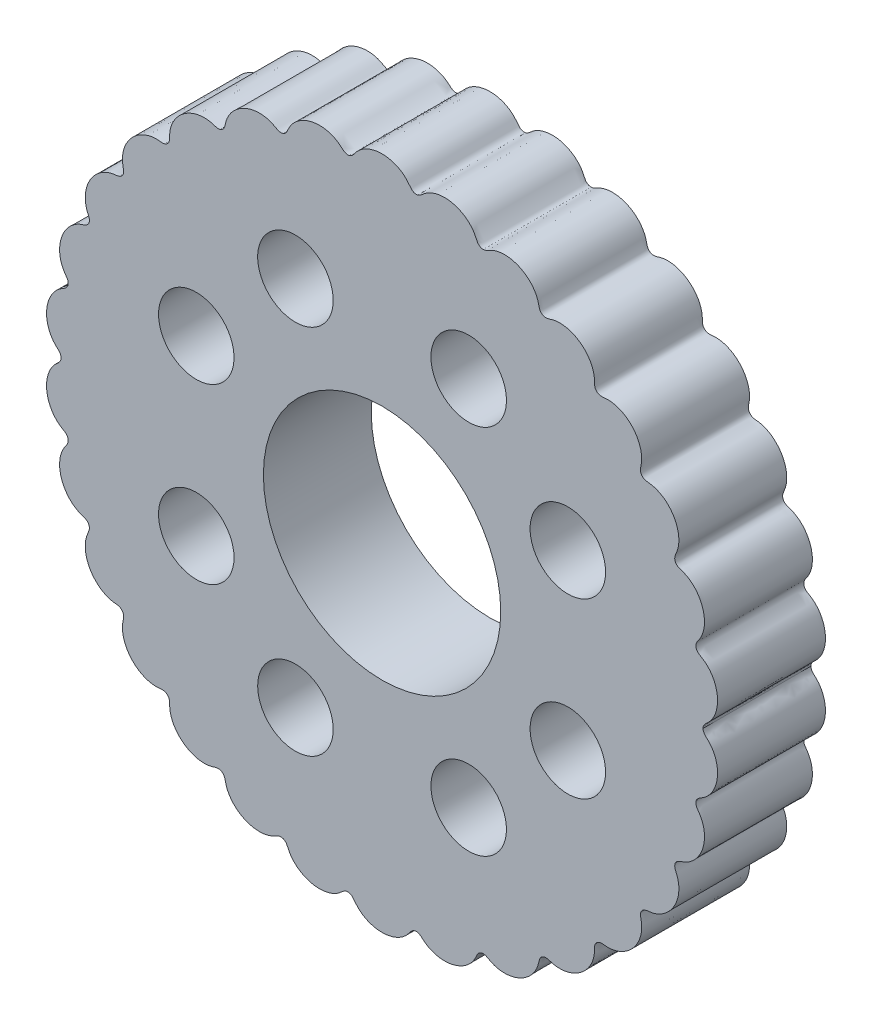
SolidWorks part; units mm, degrees
ref_plane "Plan de face" through (0, 0, 0) normal (0, 0, 1) x (1, 0, 0)
ref_plane "Plan de dessus" through (0, 0, 0) normal (0, 1, 0) x (1, 0, 0)
ref_plane "Plan de droite" through (0, 0, 0) normal (1, 0, 0) x (0, 0, -1)
sketch "Esquisse1" plane through (0, 0, 0) normal (0, 0, 1) x (1, 0, 0)
  line L0 (-1000, 0) -> (49000, 0) construction
  spline S0 degree 4 poles (29.8631, 8.2305) (29.8499, 8.1217) (29.8133, 7.9053) (29.7416, 7.64) (29.6157, 7.3353) (29.4839, 7.095) (29.3642, 6.911) (29.2467, 6.7537) (29.1538, 6.6056) (29.0902, 6.432) (29.0737, 6.2397) (29.1354, 6.023) (29.2904, 5.838) (29.4774, 5.7198) (29.6579, 5.6163) (29.8231, 5.5082) (30.0196, 5.3594) (30.2372, 5.1583) (30.5232, 4.8242) (30.8216, 4.3213) (31.0469, 3.679) (31.1337, 2.9091) (31.0567, 2.2277) (30.8902, 1.7108) (30.7109, 1.353) (30.5728, 1.1334) (30.4496, 0.9663) (30.3139, 0.8094) (30.1671, 0.6626) (30.0393, 0.549) (29.9425, 0.4546) (29.8803, 0.3777) (29.8449, 0.3262) (29.8141, 0.2716) (29.7888, 0.2141) (29.7717, 0.1632) (29.761, 0.1169) (29.7536, 0.0672) (29.7495, 0.017) (29.7494, -0.0206) (29.7556, -0.0898) (29.7678, -0.1499) (29.7904, -0.2203) (29.8284, -0.303) (29.8828, -0.3847) (29.9529, -0.4642) (30.04, -0.5488) (30.1416, -0.6407) (30.2572, -0.7512) (30.3813, -0.8854) (30.4962, -1.0277) (30.6276, -1.2147) (30.7721, -1.4641) (30.9126, -1.7829) (31.0276, -2.1744) (31.0935, -2.591) (31.107, -3.0187) (31.0662, -3.4508) (30.9693, -3.8803) (30.8145, -4.2991) (30.6117, -4.6792) (30.3965, -4.9766) (30.1917, -5.1998) (30.0146, -5.3603) (29.8643, -5.4786) (29.7061, -5.5858) (29.542, -5.684) (29.3671, -5.785) (29.2042, -5.9269) (29.0936, -6.1295) (29.0703, -6.371) (29.1391, -6.5914) (29.2598, -6.7697) (29.3791, -6.934) (29.4834, -7.0955) (29.5997, -7.3056) (29.715, -7.5703) (29.8147, -7.8969) (29.8798, -8.2857) (29.896, -8.684) (29.8631, -9.0858) (29.7829, -9.4799) (29.6574, -9.8612) (29.4885, -10.2243) (29.2783, -10.5643) (29.0303, -10.8742) (28.7824, -11.1148) (28.5506, -11.2952) (28.3468, -11.4258) (28.1768, -11.5188) (28.0006, -11.599) (27.8193, -11.6676) (27.6244, -11.7296) (27.4217, -11.8089) (27.242, -11.9571) (27.1301, -12.1734) (27.113, -12.404) (27.1707, -12.6114) (27.2542, -12.795) (27.3276, -12.9715) (27.3906, -13.1518) (27.4404, -13.3363) (27.4866, -13.5706) (27.5177, -13.8717) (27.5133, -14.2384) (27.4499, -14.6642) (27.3252, -15.0926) (27.1465, -15.4978) (26.919, -15.8739) (26.6474, -16.2153) (26.3365, -16.5168) (26.0024, -16.764) (25.654, -16.9563) (25.3418, -17.0779) (25.0791, -17.148) (24.8562, -17.1866) (24.6765, -17.2082) (24.4854, -17.2287) (24.2872, -17.2853) (24.1038, -17.4139) (23.9758, -17.6159) (23.9376, -17.8434) (23.9703, -18.0586) (24.0141, -18.2584) (24.0453, -18.4498) (24.0639, -18.6424) (24.0684, -18.8361) (24.0572, -19.0779) (24.0169, -19.3689) (23.9324, -19.7039) (23.7881, -20.0736) (23.5988, -20.4256) (23.3687, -20.7534) (23.1013, -21.0528) (22.8001, -21.3193) (22.4685, -21.5487) (22.1155, -21.7338) (21.7463, -21.8718) (21.4135, -21.9488) (21.1267, -21.9813) (20.8866, -21.9856) (20.6945, -21.9761) (20.4927, -21.9549) (20.2778, -21.9395) (20.0526, -21.9901) (19.8551, -22.131) (19.7349, -22.3281) (19.6935, -22.5401) (19.6935, -22.7421) (19.6905, -22.9333) (19.6768, -23.124) (19.6495, -23.3133) (19.599, -23.5469) (19.5081, -23.8358) (19.3582, -24.1709) (19.1304, -24.5365) (18.8451, -24.88) (18.5216, -25.1787) (18.1677, -25.4301) (17.7906, -25.6322) (17.3968, -25.7835) (17.0003, -25.8796) (16.6085, -25.9224) (16.2742, -25.9148) (16.002, -25.8785) (15.7793, -25.8278) (15.6036, -25.7769) (15.4169, -25.7147) (15.2087, -25.6689) (14.9779, -25.6954) (14.7639, -25.8189) (14.6256, -26.0056) (14.5611, -26.2088) (14.5217, -26.4015) (14.4779, -26.5791) (14.4104, -26.7974) (14.3058, -27.0513) (14.1452, -27.3445) (13.9122, -27.6625) (13.6308, -27.9579) (13.3029, -28.2232) (12.9393, -28.4488) (12.5446, -28.6295) (12.1242, -28.7604) (11.6841, -28.8357) (11.2535, -28.8501) (10.8884, -28.8124) (10.5927, -28.7466) (10.3651, -28.6736) (10.1875, -28.6026) (10.0156, -28.5191) (9.8485, -28.4261) (9.6736, -28.3252) (9.4693, -28.255) (9.2385, -28.2605) (9.0177, -28.3611) (8.8612, -28.5309) (8.7671, -28.7246) (8.6846, -28.91) (8.5968, -29.0812) (8.473, -29.2869) (8.3014, -29.519) (8.0684, -29.7687) (7.7643, -30.0195) (7.4274, -30.2327) (7.0631, -30.4051) (6.6816, -30.5327) (6.2887, -30.6146) (5.8897, -30.6499) (5.4902, -30.6379) (5.0979, -30.5781) (4.7655, -30.4837) (4.4934, -30.3731) (4.2784, -30.2619) (4.1128, -30.1612) (3.9553, -30.0487) (3.8052, -29.926) (3.6541, -29.7882) (3.484, -29.6523) (3.2679, -29.5716) (3.029, -29.5815) (2.8259, -29.676) (2.6778, -29.8193) (2.5645, -29.9746) (2.456, -30.1194) (2.311, -30.2931) (2.119, -30.4856) (1.8576, -30.6952) (1.5168, -30.9007) (1.1357, -31.0665) (0.7192, -31.185) (0.2877, -31.2495) (-0.1517, -31.2585) (-0.592, -31.2106) (-1.0254, -31.1045) (-1.4258, -30.9464) (-1.7456, -30.7669) (-1.9908, -30.5894) (-2.1706, -30.4322) (-2.3055, -30.2968) (-2.4301, -30.1521) (-2.5463, -30.0003) (-2.6635, -29.8363) (-2.8143, -29.6826) (-3.0226, -29.582) (-3.2659, -29.5708) (-3.484, -29.6523) (-3.654, -29.7882) (-3.8052, -29.926) (-3.9553, -30.0487) (-4.1128, -30.1612) (-4.2784, -30.2619) (-4.4934, -30.3731) (-4.7655, -30.4837) (-5.0979, -30.5781) (-5.4902, -30.6379) (-5.8897, -30.6499) (-6.2887, -30.6146) (-6.6816, -30.5327) (-7.0631, -30.4051) (-7.4274, -30.2327) (-7.7643, -30.0195) (-8.0684, -29.7687) (-8.3014, -29.519) (-8.473, -29.2869) (-8.5968, -29.0812) (-8.6846, -28.91) (-8.7671, -28.7246) (-8.8612, -28.5309) (-9.0177, -28.3611) (-9.2385, -28.2605) (-9.4693, -28.255) (-9.6736, -28.3252) (-9.8485, -28.4261) (-10.0156, -28.5191) (-10.1875, -28.6026) (-10.3651, -28.6736) (-10.5927, -28.7466) (-10.8884, -28.8124) (-11.2535, -28.8501) (-11.6841, -28.8357) (-12.1242, -28.7604) (-12.5446, -28.6295) (-12.9393, -28.4488) (-13.3029, -28.2232) (-13.6308, -27.9579) (-13.9122, -27.6625) (-14.1452, -27.3445) (-14.3058, -27.0513) (-14.4104, -26.7974) (-14.4779, -26.5791) (-14.5217, -26.4015) (-14.5611, -26.2088) (-14.6256, -26.0056) (-14.7639, -25.8189) (-14.9779, -25.6954) (-15.2087, -25.6689) (-15.4169, -25.7147) (-15.6036, -25.7769) (-15.7793, -25.8278) (-16.002, -25.8785) (-16.2742, -25.9148) (-16.6085, -25.9224) (-17.0003, -25.8796) (-17.3968, -25.7835) (-17.7906, -25.6322) (-18.1677, -25.4301) (-18.5216, -25.1787) (-18.8451, -24.88) (-19.1304, -24.5365) (-19.3582, -24.1709) (-19.5081, -23.8358) (-19.599, -23.5469) (-19.6495, -23.3133) (-19.6768, -23.124) (-19.6905, -22.9333) (-19.6935, -22.7421) (-19.6935, -22.5401) (-19.7349, -22.3281) (-19.8551, -22.131) (-20.0526, -21.9901) (-20.2778, -21.9395) (-20.4927, -21.9549) (-20.6945, -21.9761) (-20.8866, -21.9856) (-21.1267, -21.9813) (-21.4135, -21.9488) (-21.7463, -21.8718) (-22.1155, -21.7338) (-22.4685, -21.5487) (-22.8001, -21.3193) (-23.1013, -21.0528) (-23.3687, -20.7534) (-23.5988, -20.4256) (-23.7881, -20.0736) (-23.9324, -19.7039) (-24.0169, -19.3689) (-24.0572, -19.0779) (-24.0684, -18.8361) (-24.0639, -18.6424) (-24.0453, -18.4498) (-24.0141, -18.2584) (-23.9703, -18.0586) (-23.9376, -17.8434) (-23.9758, -17.6159) (-24.1038, -17.4139) (-24.2872, -17.2853) (-24.4854, -17.2287) (-24.6765, -17.2082) (-24.8562, -17.1866) (-25.0791, -17.148) (-25.3418, -17.0779) (-25.654, -16.9563) (-26.0024, -16.764) (-26.3365, -16.5168) (-26.6474, -16.2153) (-26.919, -15.8739) (-27.1465, -15.4978) (-27.3252, -15.0926) (-27.4499, -14.6642) (-27.5133, -14.2384) (-27.5177, -13.8717) (-27.4866, -13.5706) (-27.4404, -13.3363) (-27.3906, -13.1518) (-27.3276, -12.9715) (-27.2542, -12.795) (-27.1707, -12.6114) (-27.113, -12.404) (-27.1301, -12.1734) (-27.242, -11.9571) (-27.4217, -11.8089) (-27.6244, -11.7296) (-27.8193, -11.6676) (-28.0006, -11.599) (-28.1768, -11.5188) (-28.3468, -11.4258) (-28.5506, -11.2952) (-28.7824, -11.1148) (-29.0303, -10.8742) (-29.2783, -10.5643) (-29.4885, -10.2243) (-29.6574, -9.8612) (-29.7829, -9.4799) (-29.8631, -9.0858) (-29.896, -8.684) (-29.8798, -8.2857) (-29.8147, -7.8969) (-29.715, -7.5703) (-29.5997, -7.3056) (-29.4834, -7.0955) (-29.3791, -6.934) (-29.2598, -6.7697) (-29.1391, -6.5914) (-29.0703, -6.371) (-29.0936, -6.1295) (-29.2042, -5.9269) (-29.3671, -5.785) (-29.542, -5.684) (-29.7061, -5.5858) (-29.8643, -5.4786) (-30.0146, -5.3603) (-30.1917, -5.1998) (-30.3965, -4.9766) (-30.6117, -4.6792) (-30.8145, -4.2991) (-30.9693, -3.8803) (-31.0662, -3.4508) (-31.107, -3.0187) (-31.0935, -2.591) (-31.0276, -2.1744) (-30.9126, -1.7829) (-30.7537, -1.4222) (-30.58, -1.1364) (-30.4124, -0.919) (-30.2572, -0.7512) (-30.1416, -0.6407) (-30.04, -0.5488) (-29.9529, -0.4642) (-29.8828, -0.3847) (-29.8284, -0.303) (-29.7904, -0.2203) (-29.7678, -0.1499) (-29.7556, -0.0898) (-29.7494, -0.0206) (-29.7495, 0.0226) (-29.7561, 0.094) (-29.7693, 0.1557) (-29.7888, 0.2141) (-29.8141, 0.2716) (-29.8449, 0.3262) (-29.8803, 0.3778) (-29.9262, 0.4344) (-29.9834, 0.4947) (-30.0703, 0.5765) (-30.1854, 0.6811) (-30.3139, 0.8093) (-30.4835, 1.0056) (-30.6621, 1.2611) (-30.8291, 1.576) (-30.9678, 1.9517) (-31.0574, 2.3341) (-31.1011, 2.7166) (-31.1012, 3.1978) (-31.0148, 3.7704) (-30.8216, 4.3213) (-30.5232, 4.8242) (-30.2372, 5.1583) (-30.0196, 5.3594) (-29.8231, 5.5082) (-29.6579, 5.6163) (-29.4774, 5.7198) (-29.2904, 5.838) (-29.1354, 6.023) (-29.0737, 6.2397) (-29.0902, 6.432) (-29.1538, 6.6056) (-29.2467, 6.7537) (-29.3642, 6.911) (-29.4839, 7.095) (-29.6157, 7.3353) (-29.7416, 7.64) (-29.8133, 7.9053) (-29.8499, 8.1217) (-29.8631, 8.2305) knots 0 0 0 0 0 0.003392 0.006784 0.00848 0.010176 0.011872 0.013568 0.014566 0.015563 0.017559 0.01944 0.02132 0.022846 0.024371 0.025896 0.027421 0.030471 0.033522 0.039468 0.045414 0.051361 0.057307 0.060517 0.062121 0.063726 0.065331 0.066935 0.06854 0.070145 0.070628 0.071112 0.071596 0.07208 0.072564 0.073048 0.073289 0.073531 0.074015 0.07448 0.074945 0.07541 0.075875 0.076805 0.077735 0.078442 0.079149 0.080563 0.081977 0.083391 0.084805 0.086218 0.089046 0.092302 0.095557 0.098813 0.102069 0.105514 0.10896 0.112405 0.115851 0.118808 0.120287 0.121766 0.123244 0.124723 0.126202 0.12768 0.1295 0.131319 0.133154 0.134989 0.136475 0.137961 0.139448 0.140934 0.143906 0.146878 0.14999 0.153103 0.156215 0.159327 0.162414 0.1655 0.168586 0.171672 0.174668 0.176165 0.177663 0.179161 0.180659 0.182156 0.183654 0.185506 0.187357 0.189175 0.190994 0.192471 0.193949 0.195426 0.196904 0.198382 0.199859 0.202814 0.206257 0.2097 0.213143 0.216586 0.219928 0.22327 0.226613 0.229955 0.232755 0.235555 0.236955 0.238355 0.239755 0.241155 0.242909 0.244663 0.246515 0.248366 0.249864 0.251362 0.252859 0.254357 0.255855 0.257353 0.260348 0.263434 0.266521 0.269607 0.272693 0.275805 0.278918 0.28203 0.285143 0.288115 0.291087 0.292573 0.294059 0.295545 0.297031 0.298866 0.300701 0.302521 0.30434 0.305819 0.307297 0.308776 0.310255 0.311733 0.313212 0.31617 0.319615 0.323061 0.326506 0.329952 0.333207 0.336463 0.339719 0.342974 0.345802 0.34863 0.350043 0.351457 0.352871 0.354285 0.356145 0.358005 0.359865 0.361725 0.363139 0.364553 0.365967 0.367381 0.370208 0.373036 0.376292 0.379547 0.382803 0.386059 0.389504 0.39295 0.396395 0.399841 0.402798 0.404277 0.405755 0.407234 0.408713 0.410191 0.41167 0.41349 0.415309 0.417144 0.418979 0.420465 0.421951 0.423437 0.424923 0.427896 0.430868 0.43398 0.437092 0.440205 0.443317 0.446403 0.44949 0.452576 0.455662 0.458657 0.460155 0.461653 0.463151 0.464649 0.466146 0.467644 0.469495 0.471347 0.473101 0.474856 0.476256 0.477656 0.479056 0.480456 0.483256 0.486055 0.489398 0.49274 0.496082 0.499424 0.502867 0.50631 0.509753 0.513196 0.516151 0.517629 0.519106 0.520584 0.522061 0.523539 0.525016 0.526835 0.528653 0.530505 0.532356 0.533854 0.535351 0.536849 0.538347 0.539845 0.541343 0.544338 0.547424 0.55051 0.553597 0.556683 0.559795 0.562908 0.56602 0.569132 0.572104 0.575077 0.576563 0.578049 0.579535 0.581021 0.582856 0.584691 0.58651 0.58833 0.589809 0.591287 0.592766 0.594245 0.595723 0.597202 0.600159 0.603605 0.60705 0.610496 0.613941 0.617197 0.620453 0.623708 0.626964 0.629792 0.632619 0.634033 0.635447 0.636861 0.638275 0.640135 0.641995 0.643855 0.645715 0.647129 0.648543 0.649957 0.65137 0.654198 0.657026 0.660281 0.663537 0.666793 0.670048 0.673494 0.676939 0.680385 0.68383 0.686788 0.688267 0.689745 0.691224 0.692703 0.694181 0.69566 0.697479 0.699299 0.701134 0.702969 0.704455 0.705941 0.707427 0.708913 0.711885 0.714857 0.71797 0.721082 0.724195 0.727307 0.730393 0.733479 0.736566 0.739652 0.742647 0.744145 0.745643 0.747141 0.748638 0.750136 0.751634 0.753485 0.755337 0.757091 0.758845 0.760245 0.761645 0.763045 0.764445 0.767245 0.770045 0.773387 0.77673 0.780072 0.783414 0.786857 0.7903 0.793743 0.797186 0.800141 0.801618 0.803096 0.804574 0.806051 0.807529 0.809006 0.810825 0.812643 0.814494 0.816346 0.817844 0.819341 0.820839 0.822337 0.823835 0.825332 0.828328 0.831414 0.8345 0.837586 0.840673 0.843785 0.846897 0.85001 0.853122 0.856094 0.859066 0.860552 0.862039 0.863525 0.865011 0.866846 0.868681 0.8705 0.87232 0.873798 0.875277 0.876756 0.878234 0.879713 0.881192 0.884149 0.887595 0.89104 0.894486 0.897931 0.901187 0.904443 0.907698 0.910954 0.913782 0.916609 0.918023 0.919437 0.920851 0.921558 0.922265 0.923195 0.924125 0.92459 0.925055 0.92552 0.925985 0.926469 0.926952 0.927436 0.92792 0.928404 0.928888 0.929372 0.929855 0.930658 0.93146 0.933065 0.934669 0.936274 0.939483 0.942693 0.945666 0.948639 0.951612 0.954586 0.960532 0.966478 0.969529 0.972579 0.974104 0.975629 0.977154 0.97868 0.98056 0.982441 0.984437 0.985434 0.986432 0.988128 0.989824 0.99152 0.993216 0.996608 1 1 1 1 1 construction
  spline S1 degree 4 poles (29.75, 0) (29.75, -0.0128) (29.751, -0.0384) (29.7556, -0.0898) (29.7678, -0.1499) (29.7904, -0.2203) (29.8284, -0.303) (29.8828, -0.3847) (29.9529, -0.4642) (30.04, -0.5488) (30.1416, -0.6407) (30.2572, -0.7512) (30.3813, -0.8854) (30.4962, -1.0277) (30.6276, -1.2147) (30.7721, -1.4641) (30.9126, -1.7829) (31.0276, -2.1744) (31.0935, -2.591) (31.107, -3.0187) (31.0662, -3.4508) (30.9693, -3.8803) (30.8145, -4.2991) (30.6117, -4.6792) (30.3965, -4.9766) (30.1917, -5.1998) (30.0146, -5.3603) (29.8643, -5.4786) (29.7061, -5.5858) (29.542, -5.684) (29.3671, -5.785) (29.2042, -5.9269) (29.0936, -6.1295) (29.0703, -6.371) (29.1391, -6.5914) (29.2598, -6.7697) (29.3791, -6.934) (29.4834, -7.0955) (29.5997, -7.3056) (29.715, -7.5703) (29.8147, -7.8969) (29.8798, -8.2857) (29.896, -8.684) (29.8631, -9.0858) (29.7829, -9.4799) (29.6574, -9.8612) (29.4885, -10.2243) (29.2783, -10.5643) (29.0303, -10.8742) (28.7824, -11.1148) (28.5506, -11.2952) (28.3468, -11.4258) (28.1768, -11.5188) (28.0006, -11.599) (27.8193, -11.6676) (27.6244, -11.7296) (27.4217, -11.8089) (27.242, -11.9571) (27.1301, -12.1734) (27.113, -12.404) (27.1707, -12.6114) (27.2542, -12.795) (27.3276, -12.9715) (27.3906, -13.1518) (27.4404, -13.3363) (27.4866, -13.5706) (27.5177, -13.8717) (27.5133, -14.2384) (27.4499, -14.6642) (27.3252, -15.0926) (27.1465, -15.4978) (26.919, -15.8739) (26.6474, -16.2153) (26.3365, -16.5168) (26.0024, -16.764) (25.654, -16.9563) (25.3418, -17.0779) (25.0791, -17.148) (24.8562, -17.1866) (24.6765, -17.2082) (24.4854, -17.2287) (24.2872, -17.2853) (24.1038, -17.4139) (23.9758, -17.6159) (23.9376, -17.8434) (23.9703, -18.0586) (24.0141, -18.2584) (24.0453, -18.4498) (24.0639, -18.6424) (24.0684, -18.8361) (24.0572, -19.0779) (24.0169, -19.3689) (23.9324, -19.7039) (23.7881, -20.0736) (23.5988, -20.4256) (23.3687, -20.7534) (23.1013, -21.0528) (22.8001, -21.3193) (22.4685, -21.5487) (22.1155, -21.7338) (21.7463, -21.8718) (21.4135, -21.9488) (21.1267, -21.9813) (20.8866, -21.9856) (20.6945, -21.9761) (20.4927, -21.9549) (20.2778, -21.9395) (20.0526, -21.9901) (19.8551, -22.131) (19.7349, -22.3281) (19.6935, -22.5401) (19.6935, -22.7421) (19.6905, -22.9333) (19.6768, -23.124) (19.6495, -23.3133) (19.599, -23.5469) (19.5081, -23.8358) (19.3582, -24.1709) (19.1304, -24.5365) (18.8451, -24.88) (18.5216, -25.1787) (18.1677, -25.4301) (17.7906, -25.6322) (17.3968, -25.7835) (17.0003, -25.8796) (16.6085, -25.9224) (16.2742, -25.9148) (16.002, -25.8785) (15.7793, -25.8278) (15.6036, -25.7769) (15.4169, -25.7147) (15.2087, -25.6689) (14.9779, -25.6954) (14.7639, -25.8189) (14.6256, -26.0056) (14.5611, -26.2088) (14.5217, -26.4015) (14.4779, -26.5791) (14.4104, -26.7974) (14.3058, -27.0513) (14.1452, -27.3445) (13.9122, -27.6625) (13.6308, -27.9579) (13.3029, -28.2232) (12.9393, -28.4488) (12.5446, -28.6295) (12.1242, -28.7604) (11.6841, -28.8357) (11.2535, -28.8501) (10.8884, -28.8124) (10.5927, -28.7466) (10.3651, -28.6736) (10.1875, -28.6026) (10.0156, -28.5191) (9.8485, -28.4261) (9.6736, -28.3252) (9.4693, -28.255) (9.2385, -28.2605) (9.0177, -28.3611) (8.8612, -28.5309) (8.7671, -28.7246) (8.6846, -28.91) (8.5968, -29.0812) (8.473, -29.2869) (8.3014, -29.519) (8.0684, -29.7687) (7.7643, -30.0195) (7.4274, -30.2327) (7.0631, -30.4051) (6.6816, -30.5327) (6.2887, -30.6146) (5.8897, -30.6499) (5.4902, -30.6379) (5.0979, -30.5781) (4.7655, -30.4837) (4.4934, -30.3731) (4.2784, -30.2619) (4.1128, -30.1612) (3.9553, -30.0487) (3.8052, -29.926) (3.6541, -29.7882) (3.484, -29.6523) (3.2679, -29.5716) (3.029, -29.5815) (2.8259, -29.676) (2.6778, -29.8193) (2.5645, -29.9746) (2.456, -30.1194) (2.311, -30.2931) (2.119, -30.4856) (1.8576, -30.6952) (1.5168, -30.9007) (1.1357, -31.0665) (0.7192, -31.185) (0.2877, -31.2495) (-0.1517, -31.2585) (-0.592, -31.2106) (-1.0254, -31.1045) (-1.4258, -30.9464) (-1.7456, -30.7669) (-1.9908, -30.5894) (-2.1706, -30.4322) (-2.3055, -30.2968) (-2.4301, -30.1521) (-2.5463, -30.0003) (-2.6635, -29.8363) (-2.8143, -29.6826) (-3.0226, -29.582) (-3.2659, -29.5708) (-3.484, -29.6523) (-3.654, -29.7882) (-3.8052, -29.926) (-3.9553, -30.0487) (-4.1128, -30.1612) (-4.2784, -30.2619) (-4.4934, -30.3731) (-4.7655, -30.4837) (-5.0979, -30.5781) (-5.4902, -30.6379) (-5.8897, -30.6499) (-6.2887, -30.6146) (-6.6816, -30.5327) (-7.0631, -30.4051) (-7.4274, -30.2327) (-7.7643, -30.0195) (-8.0684, -29.7687) (-8.3014, -29.519) (-8.473, -29.2869) (-8.5968, -29.0812) (-8.6846, -28.91) (-8.7671, -28.7246) (-8.8612, -28.5309) (-9.0177, -28.3611) (-9.2385, -28.2605) (-9.4693, -28.255) (-9.6736, -28.3252) (-9.8485, -28.4261) (-10.0156, -28.5191) (-10.1875, -28.6026) (-10.3651, -28.6736) (-10.5927, -28.7466) (-10.8884, -28.8124) (-11.2535, -28.8501) (-11.6841, -28.8357) (-12.1242, -28.7604) (-12.5446, -28.6295) (-12.9393, -28.4488) (-13.3029, -28.2232) (-13.6308, -27.9579) (-13.9122, -27.6625) (-14.1452, -27.3445) (-14.3058, -27.0513) (-14.4104, -26.7974) (-14.4779, -26.5791) (-14.5217, -26.4015) (-14.5611, -26.2088) (-14.6256, -26.0056) (-14.7639, -25.8189) (-14.9779, -25.6954) (-15.2087, -25.6689) (-15.4169, -25.7147) (-15.6036, -25.7769) (-15.7793, -25.8278) (-16.002, -25.8785) (-16.2742, -25.9148) (-16.6085, -25.9224) (-17.0003, -25.8796) (-17.3968, -25.7835) (-17.7906, -25.6322) (-18.1677, -25.4301) (-18.5216, -25.1787) (-18.8451, -24.88) (-19.1304, -24.5365) (-19.3582, -24.1709) (-19.5081, -23.8358) (-19.599, -23.5469) (-19.6495, -23.3133) (-19.6768, -23.124) (-19.6905, -22.9333) (-19.6935, -22.7421) (-19.6935, -22.5401) (-19.7349, -22.3281) (-19.8551, -22.131) (-20.0526, -21.9901) (-20.2778, -21.9395) (-20.4927, -21.9549) (-20.6945, -21.9761) (-20.8866, -21.9856) (-21.1267, -21.9813) (-21.4135, -21.9488) (-21.7463, -21.8718) (-22.1155, -21.7338) (-22.4685, -21.5487) (-22.8001, -21.3193) (-23.1013, -21.0528) (-23.3687, -20.7534) (-23.5988, -20.4256) (-23.7881, -20.0736) (-23.9324, -19.7039) (-24.0169, -19.3689) (-24.0572, -19.0779) (-24.0684, -18.8361) (-24.0639, -18.6424) (-24.0453, -18.4498) (-24.0141, -18.2584) (-23.9703, -18.0586) (-23.9376, -17.8434) (-23.9758, -17.6159) (-24.1038, -17.4139) (-24.2872, -17.2853) (-24.4854, -17.2287) (-24.6765, -17.2082) (-24.8562, -17.1866) (-25.0791, -17.148) (-25.3418, -17.0779) (-25.654, -16.9563) (-26.0024, -16.764) (-26.3365, -16.5168) (-26.6474, -16.2153) (-26.919, -15.8739) (-27.1465, -15.4978) (-27.3252, -15.0926) (-27.4499, -14.6642) (-27.5133, -14.2384) (-27.5177, -13.8717) (-27.4866, -13.5706) (-27.4404, -13.3363) (-27.3906, -13.1518) (-27.3276, -12.9715) (-27.2542, -12.795) (-27.1707, -12.6114) (-27.113, -12.404) (-27.1301, -12.1734) (-27.242, -11.9571) (-27.4217, -11.8089) (-27.6244, -11.7296) (-27.8193, -11.6676) (-28.0006, -11.599) (-28.1768, -11.5188) (-28.3468, -11.4258) (-28.5506, -11.2952) (-28.7824, -11.1148) (-29.0303, -10.8742) (-29.2783, -10.5643) (-29.4885, -10.2243) (-29.6574, -9.8612) (-29.7829, -9.4799) (-29.8631, -9.0858) (-29.896, -8.684) (-29.8798, -8.2857) (-29.8147, -7.8969) (-29.715, -7.5703) (-29.5997, -7.3056) (-29.4834, -7.0955) (-29.3791, -6.934) (-29.2598, -6.7697) (-29.1391, -6.5914) (-29.0703, -6.371) (-29.0936, -6.1295) (-29.2042, -5.9269) (-29.3671, -5.785) (-29.542, -5.684) (-29.7061, -5.5858) (-29.8643, -5.4786) (-30.0146, -5.3603) (-30.1917, -5.1998) (-30.3965, -4.9766) (-30.6117, -4.6792) (-30.8145, -4.2991) (-30.9693, -3.8803) (-31.0662, -3.4508) (-31.107, -3.0187) (-31.0935, -2.591) (-31.0276, -2.1744) (-30.9126, -1.7829) (-30.7537, -1.4222) (-30.58, -1.1364) (-30.4124, -0.919) (-30.2572, -0.7512) (-30.1416, -0.6407) (-30.04, -0.5488) (-29.9529, -0.4642) (-29.8828, -0.3847) (-29.8284, -0.303) (-29.7904, -0.2203) (-29.7678, -0.1499) (-29.7556, -0.0898) (-29.751, -0.0384) (-29.75, -0.0128) (-29.75, 0) knots 0.074015 0.074015 0.074015 0.074015 0.074015 0.07448 0.074945 0.07541 0.075875 0.076805 0.077735 0.078442 0.079149 0.080563 0.081977 0.083391 0.084805 0.086218 0.089046 0.092302 0.095557 0.098813 0.102069 0.105514 0.10896 0.112405 0.115851 0.118808 0.120287 0.121766 0.123244 0.124723 0.126202 0.12768 0.1295 0.131319 0.133154 0.134989 0.136475 0.137961 0.139448 0.140934 0.143906 0.146878 0.14999 0.153103 0.156215 0.159327 0.162414 0.1655 0.168586 0.171672 0.174668 0.176165 0.177663 0.179161 0.180659 0.182156 0.183654 0.185506 0.187357 0.189175 0.190994 0.192471 0.193949 0.195426 0.196904 0.198382 0.199859 0.202814 0.206257 0.2097 0.213143 0.216586 0.219928 0.22327 0.226613 0.229955 0.232755 0.235555 0.236955 0.238355 0.239755 0.241155 0.242909 0.244663 0.246515 0.248366 0.249864 0.251362 0.252859 0.254357 0.255855 0.257353 0.260348 0.263434 0.266521 0.269607 0.272693 0.275805 0.278918 0.28203 0.285143 0.288115 0.291087 0.292573 0.294059 0.295545 0.297031 0.298866 0.300701 0.302521 0.30434 0.305819 0.307297 0.308776 0.310255 0.311733 0.313212 0.31617 0.319615 0.323061 0.326506 0.329952 0.333207 0.336463 0.339719 0.342974 0.345802 0.34863 0.350043 0.351457 0.352871 0.354285 0.356145 0.358005 0.359865 0.361725 0.363139 0.364553 0.365967 0.367381 0.370208 0.373036 0.376292 0.379547 0.382803 0.386059 0.389504 0.39295 0.396395 0.399841 0.402798 0.404277 0.405755 0.407234 0.408713 0.410191 0.41167 0.41349 0.415309 0.417144 0.418979 0.420465 0.421951 0.423437 0.424923 0.427896 0.430868 0.43398 0.437092 0.440205 0.443317 0.446403 0.44949 0.452576 0.455662 0.458657 0.460155 0.461653 0.463151 0.464649 0.466146 0.467644 0.469495 0.471347 0.473101 0.474856 0.476256 0.477656 0.479056 0.480456 0.483256 0.486055 0.489398 0.49274 0.496082 0.499424 0.502867 0.50631 0.509753 0.513196 0.516151 0.517629 0.519106 0.520584 0.522061 0.523539 0.525016 0.526835 0.528653 0.530505 0.532356 0.533854 0.535351 0.536849 0.538347 0.539845 0.541343 0.544338 0.547424 0.55051 0.553597 0.556683 0.559795 0.562908 0.56602 0.569132 0.572104 0.575077 0.576563 0.578049 0.579535 0.581021 0.582856 0.584691 0.58651 0.58833 0.589809 0.591287 0.592766 0.594245 0.595723 0.597202 0.600159 0.603605 0.60705 0.610496 0.613941 0.617197 0.620453 0.623708 0.626964 0.629792 0.632619 0.634033 0.635447 0.636861 0.638275 0.640135 0.641995 0.643855 0.645715 0.647129 0.648543 0.649957 0.65137 0.654198 0.657026 0.660281 0.663537 0.666793 0.670048 0.673494 0.676939 0.680385 0.68383 0.686788 0.688267 0.689745 0.691224 0.692703 0.694181 0.69566 0.697479 0.699299 0.701134 0.702969 0.704455 0.705941 0.707427 0.708913 0.711885 0.714857 0.71797 0.721082 0.724195 0.727307 0.730393 0.733479 0.736566 0.739652 0.742647 0.744145 0.745643 0.747141 0.748638 0.750136 0.751634 0.753485 0.755337 0.757091 0.758845 0.760245 0.761645 0.763045 0.764445 0.767245 0.770045 0.773387 0.77673 0.780072 0.783414 0.786857 0.7903 0.793743 0.797186 0.800141 0.801618 0.803096 0.804574 0.806051 0.807529 0.809006 0.810825 0.812643 0.814494 0.816346 0.817844 0.819341 0.820839 0.822337 0.823835 0.825332 0.828328 0.831414 0.8345 0.837586 0.840673 0.843785 0.846897 0.85001 0.853122 0.856094 0.859066 0.860552 0.862039 0.863525 0.865011 0.866846 0.868681 0.8705 0.87232 0.873798 0.875277 0.876756 0.878234 0.879713 0.881192 0.884149 0.887595 0.89104 0.894486 0.897931 0.901187 0.904443 0.907698 0.910954 0.913782 0.916609 0.918023 0.919437 0.920851 0.921558 0.922265 0.923195 0.924125 0.92459 0.925055 0.92552 0.925985 0.925985 0.925985 0.925985 0.925985 construction
  spline S2 degree 4 poles (29.75, 0) (29.75, 0.0128) (29.751, 0.0384) (29.7556, 0.0898) (29.7678, 0.1499) (29.7904, 0.2203) (29.8284, 0.303) (29.8828, 0.3847) (29.9529, 0.4642) (30.04, 0.5488) (30.1416, 0.6407) (30.2572, 0.7512) (30.3813, 0.8854) (30.4962, 1.0277) (30.6276, 1.2147) (30.7721, 1.4641) (30.9126, 1.7829) (31.0276, 2.1744) (31.0935, 2.591) (31.107, 3.0187) (31.0662, 3.4508) (30.9693, 3.8803) (30.8145, 4.2991) (30.6117, 4.6792) (30.3965, 4.9766) (30.1917, 5.1998) (30.0146, 5.3603) (29.8643, 5.4786) (29.7061, 5.5858) (29.542, 5.684) (29.3671, 5.785) (29.2042, 5.9269) (29.0936, 6.1295) (29.0703, 6.371) (29.1391, 6.5914) (29.2598, 6.7697) (29.3791, 6.934) (29.4834, 7.0955) (29.5997, 7.3056) (29.715, 7.5703) (29.8147, 7.8969) (29.8798, 8.2857) (29.896, 8.684) (29.8631, 9.0858) (29.7829, 9.4799) (29.6574, 9.8612) (29.4885, 10.2243) (29.2783, 10.5643) (29.0303, 10.8742) (28.7824, 11.1148) (28.5506, 11.2952) (28.3468, 11.4258) (28.1768, 11.5188) (28.0006, 11.599) (27.8193, 11.6676) (27.6244, 11.7296) (27.4217, 11.8089) (27.242, 11.9571) (27.1301, 12.1734) (27.113, 12.404) (27.1707, 12.6114) (27.2542, 12.795) (27.3276, 12.9715) (27.3906, 13.1518) (27.4404, 13.3363) (27.4866, 13.5706) (27.5177, 13.8717) (27.5133, 14.2384) (27.4499, 14.6642) (27.3252, 15.0926) (27.1465, 15.4978) (26.919, 15.8739) (26.6474, 16.2153) (26.3365, 16.5168) (26.0024, 16.764) (25.654, 16.9563) (25.3418, 17.0779) (25.0791, 17.148) (24.8562, 17.1866) (24.6765, 17.2082) (24.4854, 17.2287) (24.2872, 17.2853) (24.1038, 17.4139) (23.9758, 17.6159) (23.9376, 17.8434) (23.9703, 18.0586) (24.0141, 18.2584) (24.0453, 18.4498) (24.0639, 18.6424) (24.0684, 18.8361) (24.0572, 19.0779) (24.0169, 19.3689) (23.9324, 19.7039) (23.7881, 20.0736) (23.5988, 20.4256) (23.3687, 20.7534) (23.1013, 21.0528) (22.8001, 21.3193) (22.4685, 21.5487) (22.1155, 21.7338) (21.7463, 21.8718) (21.4135, 21.9488) (21.1267, 21.9813) (20.8866, 21.9856) (20.6945, 21.9761) (20.4927, 21.9549) (20.2778, 21.9395) (20.0526, 21.9901) (19.8551, 22.131) (19.7349, 22.3281) (19.6935, 22.5401) (19.6935, 22.7421) (19.6905, 22.9333) (19.6768, 23.124) (19.6495, 23.3133) (19.599, 23.5469) (19.5081, 23.8358) (19.3582, 24.1709) (19.1304, 24.5365) (18.8451, 24.88) (18.5216, 25.1787) (18.1677, 25.4301) (17.7906, 25.6322) (17.3968, 25.7835) (17.0003, 25.8796) (16.6085, 25.9224) (16.2742, 25.9148) (16.002, 25.8785) (15.7793, 25.8278) (15.6036, 25.7769) (15.4169, 25.7147) (15.2087, 25.6689) (14.9779, 25.6954) (14.7639, 25.8189) (14.6256, 26.0056) (14.5611, 26.2088) (14.5217, 26.4015) (14.4779, 26.5791) (14.4104, 26.7974) (14.3058, 27.0513) (14.1452, 27.3445) (13.9122, 27.6625) (13.6308, 27.9579) (13.3029, 28.2232) (12.9393, 28.4488) (12.5446, 28.6295) (12.1242, 28.7604) (11.6841, 28.8357) (11.2535, 28.8501) (10.8884, 28.8124) (10.5927, 28.7466) (10.3651, 28.6736) (10.1875, 28.6026) (10.0156, 28.5191) (9.8485, 28.4261) (9.6736, 28.3252) (9.4693, 28.255) (9.2385, 28.2605) (9.0177, 28.3611) (8.8612, 28.5309) (8.7671, 28.7246) (8.6846, 28.91) (8.5968, 29.0812) (8.473, 29.2869) (8.3014, 29.519) (8.0684, 29.7687) (7.7643, 30.0195) (7.4274, 30.2327) (7.0631, 30.4051) (6.6816, 30.5327) (6.2887, 30.6146) (5.8897, 30.6499) (5.4902, 30.6379) (5.0979, 30.5781) (4.7655, 30.4837) (4.4934, 30.3731) (4.2784, 30.2619) (4.1128, 30.1612) (3.9553, 30.0487) (3.8052, 29.926) (3.6541, 29.7882) (3.484, 29.6523) (3.2679, 29.5716) (3.029, 29.5815) (2.8259, 29.676) (2.6778, 29.8193) (2.5645, 29.9746) (2.456, 30.1194) (2.311, 30.2931) (2.119, 30.4856) (1.8576, 30.6952) (1.5168, 30.9007) (1.1357, 31.0665) (0.7192, 31.185) (0.2877, 31.2495) (-0.1517, 31.2585) (-0.592, 31.2106) (-1.0254, 31.1045) (-1.4258, 30.9464) (-1.7456, 30.7669) (-1.9908, 30.5894) (-2.1706, 30.4322) (-2.3055, 30.2968) (-2.4301, 30.1521) (-2.5463, 30.0003) (-2.6635, 29.8363) (-2.8143, 29.6826) (-3.0226, 29.582) (-3.2659, 29.5708) (-3.484, 29.6523) (-3.654, 29.7882) (-3.8052, 29.926) (-3.9553, 30.0487) (-4.1128, 30.1612) (-4.2784, 30.2619) (-4.4934, 30.3731) (-4.7655, 30.4837) (-5.0979, 30.5781) (-5.4902, 30.6379) (-5.8897, 30.6499) (-6.2887, 30.6146) (-6.6816, 30.5327) (-7.0631, 30.4051) (-7.4274, 30.2327) (-7.7643, 30.0195) (-8.0684, 29.7687) (-8.3014, 29.519) (-8.473, 29.2869) (-8.5968, 29.0812) (-8.6846, 28.91) (-8.7671, 28.7246) (-8.8612, 28.5309) (-9.0177, 28.3611) (-9.2385, 28.2605) (-9.4693, 28.255) (-9.6736, 28.3252) (-9.8485, 28.4261) (-10.0156, 28.5191) (-10.1875, 28.6026) (-10.3651, 28.6736) (-10.5927, 28.7466) (-10.8884, 28.8124) (-11.2535, 28.8501) (-11.6841, 28.8357) (-12.1242, 28.7604) (-12.5446, 28.6295) (-12.9393, 28.4488) (-13.3029, 28.2232) (-13.6308, 27.9579) (-13.9122, 27.6625) (-14.1452, 27.3445) (-14.3058, 27.0513) (-14.4104, 26.7974) (-14.4779, 26.5791) (-14.5217, 26.4015) (-14.5611, 26.2088) (-14.6256, 26.0056) (-14.7639, 25.8189) (-14.9779, 25.6954) (-15.2087, 25.6689) (-15.4169, 25.7147) (-15.6036, 25.7769) (-15.7793, 25.8278) (-16.002, 25.8785) (-16.2742, 25.9148) (-16.6085, 25.9224) (-17.0003, 25.8796) (-17.3968, 25.7835) (-17.7906, 25.6322) (-18.1677, 25.4301) (-18.5216, 25.1787) (-18.8451, 24.88) (-19.1304, 24.5365) (-19.3582, 24.1709) (-19.5081, 23.8358) (-19.599, 23.5469) (-19.6495, 23.3133) (-19.6768, 23.124) (-19.6905, 22.9333) (-19.6935, 22.7421) (-19.6935, 22.5401) (-19.7349, 22.3281) (-19.8551, 22.131) (-20.0526, 21.9901) (-20.2778, 21.9395) (-20.4927, 21.9549) (-20.6945, 21.9761) (-20.8866, 21.9856) (-21.1267, 21.9813) (-21.4135, 21.9488) (-21.7463, 21.8718) (-22.1155, 21.7338) (-22.4685, 21.5487) (-22.8001, 21.3193) (-23.1013, 21.0528) (-23.3687, 20.7534) (-23.5988, 20.4256) (-23.7881, 20.0736) (-23.9324, 19.7039) (-24.0169, 19.3689) (-24.0572, 19.0779) (-24.0684, 18.8361) (-24.0639, 18.6424) (-24.0453, 18.4498) (-24.0141, 18.2584) (-23.9703, 18.0586) (-23.9376, 17.8434) (-23.9758, 17.6159) (-24.1038, 17.4139) (-24.2872, 17.2853) (-24.4854, 17.2287) (-24.6765, 17.2082) (-24.8562, 17.1866) (-25.0791, 17.148) (-25.3418, 17.0779) (-25.654, 16.9563) (-26.0024, 16.764) (-26.3365, 16.5168) (-26.6474, 16.2153) (-26.919, 15.8739) (-27.1465, 15.4978) (-27.3252, 15.0926) (-27.4499, 14.6642) (-27.5133, 14.2384) (-27.5177, 13.8717) (-27.4866, 13.5706) (-27.4404, 13.3363) (-27.3906, 13.1518) (-27.3276, 12.9715) (-27.2542, 12.795) (-27.1707, 12.6114) (-27.113, 12.404) (-27.1301, 12.1734) (-27.242, 11.9571) (-27.4217, 11.8089) (-27.6244, 11.7296) (-27.8193, 11.6676) (-28.0006, 11.599) (-28.1768, 11.5188) (-28.3468, 11.4258) (-28.5506, 11.2952) (-28.7824, 11.1148) (-29.0303, 10.8742) (-29.2783, 10.5643) (-29.4885, 10.2243) (-29.6574, 9.8612) (-29.7829, 9.4799) (-29.8631, 9.0858) (-29.896, 8.684) (-29.8798, 8.2857) (-29.8147, 7.8969) (-29.715, 7.5703) (-29.5997, 7.3056) (-29.4834, 7.0955) (-29.3791, 6.934) (-29.2598, 6.7697) (-29.1391, 6.5914) (-29.0703, 6.371) (-29.0936, 6.1295) (-29.2042, 5.9269) (-29.3671, 5.785) (-29.542, 5.684) (-29.7061, 5.5858) (-29.8643, 5.4786) (-30.0146, 5.3603) (-30.1917, 5.1998) (-30.3965, 4.9766) (-30.6117, 4.6792) (-30.8145, 4.2991) (-30.9693, 3.8803) (-31.0662, 3.4508) (-31.107, 3.0187) (-31.0935, 2.591) (-31.0276, 2.1744) (-30.9126, 1.7829) (-30.7537, 1.4222) (-30.58, 1.1364) (-30.4124, 0.919) (-30.2572, 0.7512) (-30.1416, 0.6407) (-30.04, 0.5488) (-29.9529, 0.4642) (-29.8828, 0.3847) (-29.8284, 0.303) (-29.7904, 0.2203) (-29.7678, 0.1499) (-29.7556, 0.0898) (-29.751, 0.0384) (-29.75, 0.0128) (-29.75, 0) knots 0.074015 0.074015 0.074015 0.074015 0.074015 0.07448 0.074945 0.07541 0.075875 0.076805 0.077735 0.078442 0.079149 0.080563 0.081977 0.083391 0.084805 0.086218 0.089046 0.092302 0.095557 0.098813 0.102069 0.105514 0.10896 0.112405 0.115851 0.118808 0.120287 0.121766 0.123244 0.124723 0.126202 0.12768 0.1295 0.131319 0.133154 0.134989 0.136475 0.137961 0.139448 0.140934 0.143906 0.146878 0.14999 0.153103 0.156215 0.159327 0.162414 0.1655 0.168586 0.171672 0.174668 0.176165 0.177663 0.179161 0.180659 0.182156 0.183654 0.185506 0.187357 0.189175 0.190994 0.192471 0.193949 0.195426 0.196904 0.198382 0.199859 0.202814 0.206257 0.2097 0.213143 0.216586 0.219928 0.22327 0.226613 0.229955 0.232755 0.235555 0.236955 0.238355 0.239755 0.241155 0.242909 0.244663 0.246515 0.248366 0.249864 0.251362 0.252859 0.254357 0.255855 0.257353 0.260348 0.263434 0.266521 0.269607 0.272693 0.275805 0.278918 0.28203 0.285143 0.288115 0.291087 0.292573 0.294059 0.295545 0.297031 0.298866 0.300701 0.302521 0.30434 0.305819 0.307297 0.308776 0.310255 0.311733 0.313212 0.31617 0.319615 0.323061 0.326506 0.329952 0.333207 0.336463 0.339719 0.342974 0.345802 0.34863 0.350043 0.351457 0.352871 0.354285 0.356145 0.358005 0.359865 0.361725 0.363139 0.364553 0.365967 0.367381 0.370208 0.373036 0.376292 0.379547 0.382803 0.386059 0.389504 0.39295 0.396395 0.399841 0.402798 0.404277 0.405755 0.407234 0.408713 0.410191 0.41167 0.41349 0.415309 0.417144 0.418979 0.420465 0.421951 0.423437 0.424923 0.427896 0.430868 0.43398 0.437092 0.440205 0.443317 0.446403 0.44949 0.452576 0.455662 0.458657 0.460155 0.461653 0.463151 0.464649 0.466146 0.467644 0.469495 0.471347 0.473101 0.474856 0.476256 0.477656 0.479056 0.480456 0.483256 0.486055 0.489398 0.49274 0.496082 0.499424 0.502867 0.50631 0.509753 0.513196 0.516151 0.517629 0.519106 0.520584 0.522061 0.523539 0.525016 0.526835 0.528653 0.530505 0.532356 0.533854 0.535351 0.536849 0.538347 0.539845 0.541343 0.544338 0.547424 0.55051 0.553597 0.556683 0.559795 0.562908 0.56602 0.569132 0.572104 0.575077 0.576563 0.578049 0.579535 0.581021 0.582856 0.584691 0.58651 0.58833 0.589809 0.591287 0.592766 0.594245 0.595723 0.597202 0.600159 0.603605 0.60705 0.610496 0.613941 0.617197 0.620453 0.623708 0.626964 0.629792 0.632619 0.634033 0.635447 0.636861 0.638275 0.640135 0.641995 0.643855 0.645715 0.647129 0.648543 0.649957 0.65137 0.654198 0.657026 0.660281 0.663537 0.666793 0.670048 0.673494 0.676939 0.680385 0.68383 0.686788 0.688267 0.689745 0.691224 0.692703 0.694181 0.69566 0.697479 0.699299 0.701134 0.702969 0.704455 0.705941 0.707427 0.708913 0.711885 0.714857 0.71797 0.721082 0.724195 0.727307 0.730393 0.733479 0.736566 0.739652 0.742647 0.744145 0.745643 0.747141 0.748638 0.750136 0.751634 0.753485 0.755337 0.757091 0.758845 0.760245 0.761645 0.763045 0.764445 0.767245 0.770045 0.773387 0.77673 0.780072 0.783414 0.786857 0.7903 0.793743 0.797186 0.800141 0.801618 0.803096 0.804574 0.806051 0.807529 0.809006 0.810825 0.812643 0.814494 0.816346 0.817844 0.819341 0.820839 0.822337 0.823835 0.825332 0.828328 0.831414 0.8345 0.837586 0.840673 0.843785 0.846897 0.85001 0.853122 0.856094 0.859066 0.860552 0.862039 0.863525 0.865011 0.866846 0.868681 0.8705 0.87232 0.873798 0.875277 0.876756 0.878234 0.879713 0.881192 0.884149 0.887595 0.89104 0.894486 0.897931 0.901187 0.904443 0.907698 0.910954 0.913782 0.916609 0.918023 0.919437 0.920851 0.921558 0.922265 0.923195 0.924125 0.92459 0.925055 0.92552 0.925985 0.925985 0.925985 0.925985 0.925985 construction
  spline S3 degree 1 poles (29.75, 0) (-29.75, 0) knots 0 0 1 1 construction
  spline S4 degree 1 poles (29.75, 0) (-29.75, 0) knots 0 0 1 1 construction
  spline S5 degree 3 poles (29.75, 0) (29.75, -0.1406) (29.8681, -0.4215) (30.3237, -0.7786) (30.7561, -1.3606) (31.0553, -2.1754) (31.1312, -3.0392) (30.9906, -3.8945) (30.6973, -4.5551) (30.3619, -5.0221) (30.0608, -5.3306) (29.7178, -5.5927) (29.3285, -5.7822) (29.0498, -6.1414) (29.1116, -6.5971) (29.3899, -6.9321) (29.6058, -7.3046) (29.7633, -7.7062) (29.8906, -8.2668) (29.9024, -8.9897) (29.697, -9.8317) (29.2892, -10.5973) (28.6961, -11.2292) (28.0717, -11.6031) (27.5139, -11.7453) (27.1536, -12.0183) (27.0946, -12.4769) (27.2941, -12.8656) (27.4333, -13.2722) (27.5329, -13.8391) (27.4964, -14.5618) (27.2288, -15.3865) (26.7645, -16.1184) (26.2365, -16.6119) (25.7456, -16.9114) (25.3486, -17.0786) (24.9302, -17.1884) (24.5002, -17.2071) (24.0838, -17.3778) (23.9068, -17.8074) (24.0152, -18.2318) (24.0734, -18.6569) (24.0621, -19.0887) (23.9614, -19.6545) (23.6897, -20.3247) (23.1712, -21.0193) (22.6089, -21.4728) (22.1, -21.7402) (21.56, -21.9344) (20.9823, -22.0179) (20.416, -21.9307) (19.972, -21.9884) (19.6885, -22.359) (19.6979, -22.798) (19.6732, -23.2258) (19.5437, -23.7874) (19.2292, -24.4386) (18.66, -25.0931) (17.9464, -25.5846) (17.1314, -25.883) (16.4108, -25.938) (15.8395, -25.8558) (15.4373, -25.7077) (14.9947, -25.6514) (14.6235, -25.9366) (14.5308, -26.3668) (14.4248, -26.7815) (14.2456, -27.1752) (13.9332, -27.6573) (13.421, -28.1682) (12.6722, -28.6043) (11.8378, -28.8417) (10.9721, -28.8554) (10.2666, -28.6694) (9.7784, -28.373) (9.3657, -28.2077) (8.9323, -28.3874) (8.7402, -28.7846) (8.5569, -29.1709) (8.2183, -29.638) (7.6755, -30.1156) (6.8955, -30.4952) (6.0465, -30.6683) (5.1798, -30.6241) (4.4944, -30.3949) (4.0002, -30.0967) (3.6851, -29.8077) (3.3269, -29.5462) (2.8612, -29.6075) (2.579, -29.9478) (2.2393, -30.4063) (1.6634, -30.8531) (0.8604, -31.1778) (0, -31.2861) (-0.8604, -31.1779) (-1.6633, -30.8531) (-2.2393, -30.4063) (-2.579, -29.9477) (-2.8612, -29.6075) (-3.3269, -29.5462) (-3.6851, -29.8077) (-4.0002, -30.0967) (-4.4944, -30.3949) (-5.1798, -30.6241) (-6.0465, -30.6683) (-6.8955, -30.4952) (-7.6755, -30.1156) (-8.2183, -29.638) (-8.5569, -29.1709) (-8.7402, -28.7846) (-8.9323, -28.3874) (-9.3657, -28.2077) (-9.7784, -28.373) (-10.2666, -28.6694) (-10.9721, -28.8554) (-11.8378, -28.8417) (-12.6722, -28.6043) (-13.421, -28.1682) (-13.9332, -27.6573) (-14.2456, -27.1752) (-14.4248, -26.7815) (-14.5308, -26.3668) (-14.6235, -25.9366) (-14.9947, -25.6514) (-15.4373, -25.7077) (-15.8395, -25.8558) (-16.4108, -25.938) (-17.1314, -25.883) (-17.9464, -25.5846) (-18.66, -25.0931) (-19.2292, -24.4386) (-19.5437, -23.7874) (-19.6732, -23.2258) (-19.6979, -22.798) (-19.6885, -22.359) (-19.972, -21.9884) (-20.416, -21.9307) (-20.9823, -22.0179) (-21.56, -21.9344) (-22.1, -21.7402) (-22.6089, -21.4728) (-23.1712, -21.0193) (-23.6897, -20.3247) (-23.9614, -19.6545) (-24.0621, -19.0887) (-24.0734, -18.6569) (-24.0152, -18.2318) (-23.9068, -17.8074) (-24.0838, -17.3778) (-24.5002, -17.2071) (-24.9302, -17.1884) (-25.3486, -17.0786) (-25.7456, -16.9114) (-26.2365, -16.6119) (-26.7645, -16.1184) (-27.2288, -15.3865) (-27.4964, -14.5618) (-27.5329, -13.8391) (-27.4333, -13.2722) (-27.2941, -12.8656) (-27.0946, -12.4769) (-27.1536, -12.0183) (-27.5139, -11.7453) (-28.0717, -11.6031) (-28.6961, -11.2292) (-29.2892, -10.5973) (-29.697, -9.8317) (-29.9024, -8.9897) (-29.8906, -8.2668) (-29.7633, -7.7062) (-29.6058, -7.3046) (-29.3899, -6.9321) (-29.1116, -6.5971) (-29.0498, -6.1414) (-29.3285, -5.7822) (-29.7178, -5.5927) (-30.0608, -5.3306) (-30.3619, -5.0221) (-30.6973, -4.5551) (-30.9906, -3.8945) (-31.1312, -3.0392) (-31.0553, -2.1754) (-30.7561, -1.3606) (-30.3237, -0.7786) (-29.8681, -0.4215) (-29.75, -0.1406) (-29.75, 0) knots 0.074015 0.074015 0.074015 0.074015 0.077343 0.080671 0.087327 0.093983 0.100639 0.107295 0.113951 0.117279 0.120607 0.123935 0.127263 0.130591 0.133919 0.137247 0.140575 0.143903 0.147231 0.153887 0.160543 0.167199 0.173855 0.180511 0.183839 0.187167 0.190495 0.193823 0.197151 0.200479 0.207135 0.213792 0.220448 0.227104 0.230432 0.23376 0.237088 0.240416 0.243744 0.247072 0.2504 0.253728 0.257056 0.260384 0.26704 0.273696 0.280352 0.28368 0.287008 0.293664 0.296992 0.30032 0.303648 0.306976 0.310304 0.313632 0.320288 0.326944 0.3336 0.340256 0.346912 0.35024 0.353568 0.356896 0.360224 0.363552 0.36688 0.370208 0.373536 0.380192 0.386848 0.393504 0.40016 0.406816 0.410144 0.413472 0.4168 0.420128 0.423456 0.426784 0.43344 0.440096 0.446752 0.453408 0.460064 0.463392 0.46672 0.470048 0.473376 0.476704 0.480032 0.486688 0.493344 0.5 0.506656 0.513312 0.519968 0.523296 0.526624 0.529952 0.53328 0.536608 0.539936 0.546592 0.553248 0.559904 0.56656 0.573216 0.576544 0.579872 0.5832 0.586528 0.589856 0.593184 0.59984 0.606496 0.613152 0.619808 0.626464 0.629792 0.63312 0.636448 0.639776 0.643104 0.646432 0.64976 0.653088 0.659744 0.6664 0.673056 0.679712 0.686368 0.689696 0.693024 0.696352 0.69968 0.703008 0.706336 0.712992 0.71632 0.719648 0.726304 0.73296 0.739616 0.742944 0.746272 0.7496 0.752928 0.756256 0.759584 0.762912 0.76624 0.769568 0.772896 0.779552 0.786208 0.792865 0.799521 0.802849 0.806177 0.809505 0.812833 0.816161 0.819489 0.826145 0.832801 0.839457 0.846113 0.852769 0.856097 0.859425 0.862753 0.866081 0.869409 0.872737 0.876065 0.879393 0.882721 0.886049 0.892705 0.899361 0.906017 0.912673 0.919329 0.922657 0.925985 0.925985 0.925985 0.925985
  spline S6 degree 3 poles (-29.75, 0) (-29.75, 0.1406) (-29.8681, 0.4215) (-30.3237, 0.7786) (-30.7561, 1.3606) (-31.0553, 2.1754) (-31.1312, 3.0392) (-30.9906, 3.8945) (-30.6973, 4.5551) (-30.3619, 5.0221) (-30.0608, 5.3306) (-29.7178, 5.5927) (-29.3285, 5.7822) (-29.0498, 6.1414) (-29.1116, 6.5971) (-29.3899, 6.9321) (-29.6058, 7.3046) (-29.7633, 7.7062) (-29.8906, 8.2668) (-29.9024, 8.9897) (-29.697, 9.8317) (-29.2892, 10.5973) (-28.6961, 11.2292) (-28.0717, 11.6031) (-27.5139, 11.7453) (-27.1536, 12.0183) (-27.0946, 12.4769) (-27.2941, 12.8656) (-27.4333, 13.2722) (-27.5329, 13.8391) (-27.4964, 14.5618) (-27.2288, 15.3865) (-26.7645, 16.1184) (-26.2365, 16.6119) (-25.7456, 16.9114) (-25.3486, 17.0786) (-24.9302, 17.1884) (-24.5002, 17.2071) (-24.0838, 17.3778) (-23.9068, 17.8074) (-24.0152, 18.2318) (-24.0734, 18.6569) (-24.0621, 19.0887) (-23.9614, 19.6545) (-23.6897, 20.3247) (-23.1712, 21.0193) (-22.6089, 21.4728) (-22.1, 21.7402) (-21.56, 21.9344) (-20.9823, 22.0179) (-20.416, 21.9307) (-19.972, 21.9884) (-19.6885, 22.359) (-19.6979, 22.798) (-19.6732, 23.2258) (-19.5437, 23.7874) (-19.2292, 24.4386) (-18.66, 25.0931) (-17.9464, 25.5846) (-17.1314, 25.883) (-16.4108, 25.938) (-15.8395, 25.8558) (-15.4373, 25.7077) (-14.9947, 25.6514) (-14.6235, 25.9366) (-14.5308, 26.3668) (-14.4248, 26.7815) (-14.2456, 27.1752) (-13.9332, 27.6573) (-13.421, 28.1682) (-12.6722, 28.6043) (-11.8378, 28.8417) (-10.9721, 28.8554) (-10.2666, 28.6694) (-9.7784, 28.373) (-9.3657, 28.2077) (-8.9323, 28.3874) (-8.7402, 28.7846) (-8.5569, 29.1709) (-8.2183, 29.638) (-7.6755, 30.1156) (-6.8955, 30.4952) (-6.0465, 30.6683) (-5.1798, 30.6241) (-4.4944, 30.3949) (-4.0002, 30.0967) (-3.6851, 29.8077) (-3.3269, 29.5462) (-2.8612, 29.6075) (-2.579, 29.9477) (-2.2393, 30.4063) (-1.6633, 30.8531) (-0.8604, 31.1779) (0, 31.2861) (0.8604, 31.1778) (1.6634, 30.8531) (2.2393, 30.4063) (2.579, 29.9478) (2.8612, 29.6075) (3.3269, 29.5462) (3.6851, 29.8077) (4.0002, 30.0967) (4.4944, 30.3949) (5.1798, 30.6241) (6.0465, 30.6683) (6.8955, 30.4952) (7.6755, 30.1156) (8.2183, 29.638) (8.5569, 29.1709) (8.7402, 28.7846) (8.9323, 28.3874) (9.3657, 28.2077) (9.7784, 28.373) (10.2666, 28.6694) (10.9721, 28.8554) (11.8378, 28.8417) (12.6722, 28.6043) (13.421, 28.1682) (13.9332, 27.6573) (14.2456, 27.1752) (14.4248, 26.7815) (14.5308, 26.3668) (14.6235, 25.9366) (14.9947, 25.6514) (15.4373, 25.7077) (15.8395, 25.8558) (16.4108, 25.938) (17.1314, 25.883) (17.9464, 25.5846) (18.66, 25.0931) (19.2292, 24.4386) (19.5437, 23.7874) (19.6732, 23.2258) (19.6979, 22.798) (19.6885, 22.359) (19.972, 21.9884) (20.416, 21.9307) (20.9823, 22.0179) (21.56, 21.9344) (22.1, 21.7402) (22.6089, 21.4728) (23.1712, 21.0193) (23.6897, 20.3247) (23.9614, 19.6545) (24.0621, 19.0887) (24.0734, 18.6569) (24.0152, 18.2318) (23.9068, 17.8074) (24.0838, 17.3778) (24.5002, 17.2071) (24.9302, 17.1884) (25.3486, 17.0786) (25.7456, 16.9114) (26.2365, 16.6119) (26.7645, 16.1184) (27.2288, 15.3865) (27.4964, 14.5618) (27.5329, 13.8391) (27.4333, 13.2722) (27.2941, 12.8656) (27.0946, 12.4769) (27.1536, 12.0183) (27.5139, 11.7453) (28.0717, 11.6031) (28.6961, 11.2292) (29.2892, 10.5973) (29.697, 9.8317) (29.9024, 8.9897) (29.8906, 8.2668) (29.7633, 7.7062) (29.6058, 7.3046) (29.3899, 6.9321) (29.1116, 6.5971) (29.0498, 6.1414) (29.3285, 5.7822) (29.7178, 5.5927) (30.0608, 5.3306) (30.3619, 5.0221) (30.6973, 4.5551) (30.9906, 3.8945) (31.1312, 3.0392) (31.0553, 2.1754) (30.7561, 1.3606) (30.3237, 0.7786) (29.8681, 0.4215) (29.75, 0.1406) (29.75, 0) knots 0.074015 0.074015 0.074015 0.074015 0.077343 0.080671 0.087327 0.093983 0.100639 0.107295 0.113951 0.117279 0.120607 0.123935 0.127263 0.130591 0.133919 0.137247 0.140575 0.143903 0.147231 0.153887 0.160543 0.167199 0.173855 0.180511 0.183839 0.187167 0.190495 0.193823 0.197151 0.200479 0.207135 0.213792 0.220448 0.227104 0.230432 0.23376 0.237088 0.240416 0.243744 0.247072 0.2504 0.253728 0.257056 0.260384 0.26704 0.273696 0.280352 0.28368 0.287008 0.293664 0.296992 0.30032 0.303648 0.306976 0.310304 0.313632 0.320288 0.326944 0.3336 0.340256 0.346912 0.35024 0.353568 0.356896 0.360224 0.363552 0.36688 0.370208 0.373536 0.380192 0.386848 0.393504 0.40016 0.406816 0.410144 0.413472 0.4168 0.420128 0.423456 0.426784 0.43344 0.440096 0.446752 0.453408 0.460064 0.463392 0.46672 0.470048 0.473376 0.476704 0.480032 0.486688 0.493344 0.5 0.506656 0.513312 0.519968 0.523296 0.526624 0.529952 0.53328 0.536608 0.539936 0.546592 0.553248 0.559904 0.56656 0.573216 0.576544 0.579872 0.5832 0.586528 0.589856 0.593184 0.59984 0.606496 0.613152 0.619808 0.626464 0.629792 0.63312 0.636448 0.639776 0.643104 0.646432 0.64976 0.653088 0.659744 0.6664 0.673056 0.679712 0.686368 0.689696 0.693024 0.696352 0.69968 0.703008 0.706336 0.712992 0.71632 0.719648 0.726304 0.73296 0.739616 0.742944 0.746272 0.7496 0.752928 0.756256 0.759584 0.762912 0.76624 0.769568 0.772896 0.779552 0.786208 0.792865 0.799521 0.802849 0.806177 0.809505 0.812833 0.816161 0.819489 0.826145 0.832801 0.839457 0.846113 0.852769 0.856097 0.859425 0.862753 0.866081 0.869409 0.872737 0.876065 0.879393 0.882721 0.886049 0.892705 0.899361 0.906017 0.912673 0.919329 0.922657 0.925985 0.925985 0.925985 0.925985
  dimension "D1" = 0
extrude "Boss.-Extru.1" add sketch "Esquisse1" along normal blind 10
sketch "Esquisse2" plane through (0, 0, 10) normal (0, 0, 1) x (1, 0, 0)
  line L0 (0, -1000) -> (0, 49000) construction
  line L1 (0, 0) -> (-21130.9131, 45315.3894) construction
  circle A9 centre (-8.0297, 17.2198) radius 3.5
  circle A10 centre (8.0297, 17.2198) radius 3.5
  circle A11 centre (17.2198, 8.0297) radius 3.5
  circle A12 centre (17.2198, -8.0297) radius 3.5
  circle A13 centre (8.0297, -17.2198) radius 3.5
  circle A14 centre (-8.0297, -17.2198) radius 3.5
  circle A15 centre (-17.2198, -8.0297) radius 3.5
  circle A16 centre (-17.2198, 8.0297) radius 3.5
  circle A17 centre (0, 0) radius 11
  point P24 (0, 0)
  dimension "D1" = 25
  dimension "D2" = 7
  dimension "D4" = 22
  dimension "D3" = 19
extrude "Enlèv. mat.-Extru.1" cut sketch "Esquisse2" against normal through all
equation "\"R\"= 31'Radius of the rotor"
equation "\"E\"= 0.75'Eccentricity from input shaft to center of rotor"
equation "\"Rr\"= 0.5'Roller radius"
equation "\"N\"= 31'Amount of rollers"
